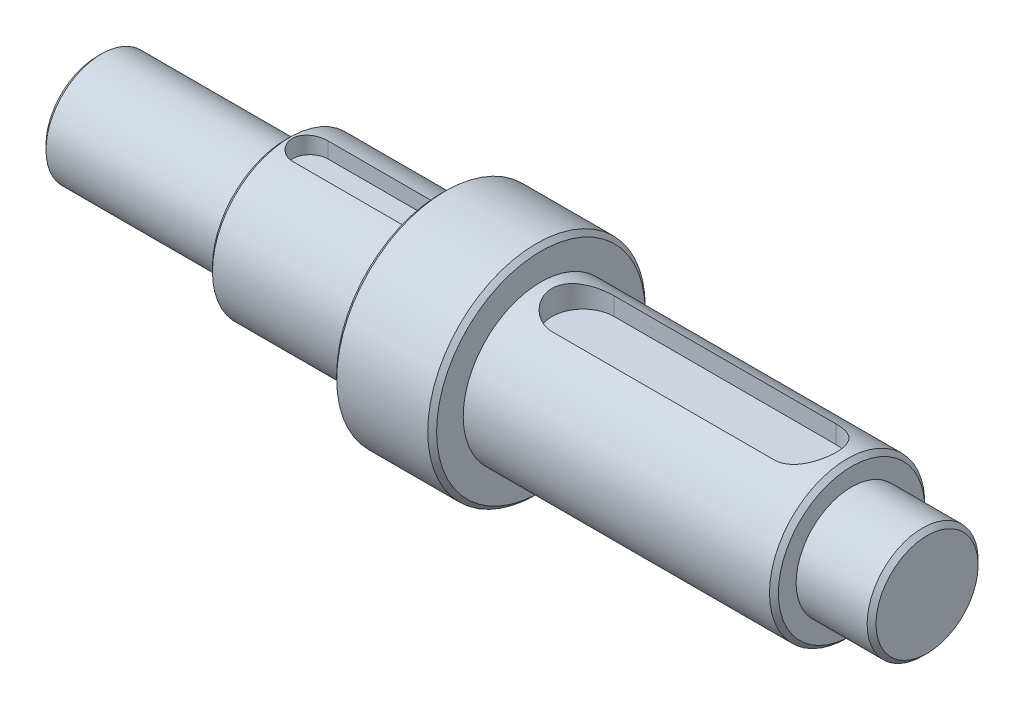
SolidWorks part; units mm, degrees
ref_plane "Front Plane" through (0, 0, 0) normal (0, 0, 1) x (1, 0, 0)
ref_plane "Top Plane" through (0, 0, 0) normal (0, 1, 0) x (1, 0, 0)
ref_plane "Right Plane" through (0, 0, 0) normal (1, 0, 0) x (0, 0, -1)
sketch "Sketch1" plane through (0, 0, 0) normal (0, 0, 1) x (1, 0, 0)
  line L0 (-92.2274, 0) -> (191.9279, 0) construction
  line L1 (-68.9095, 0) -> (-68.9095, 11.5)
  line L2 (-67.9095, 12.5) -> (-26.4095, 12.5)
  line L3 (118.0905, 11.5) -> (118.0905, 0)
  line L4 (-26.4095, 12.5) -> (-26.4095, 16.5)
  line L5 (-25.4095, 17.5) -> (8.5905, 17.5)
  line L6 (8.5905, 17.5) -> (8.5905, 23.5)
  line L7 (9.5905, 24.5) -> (30.0905, 24.5)
  line L8 (31.0905, 23.5) -> (31.0905, 17.5)
  line L9 (31.0905, 17.5) -> (100.0905, 17.5)
  line L10 (101.0905, 16.5) -> (101.0905, 12.5)
  line L11 (101.0905, 12.5) -> (117.0905, 12.5)
  line L12 (-68.9095, 11.5) -> (-67.9095, 12.5)
  line L13 (-26.4095, 16.5) -> (-25.4095, 17.5)
  line L14 (8.5905, 23.5) -> (9.5905, 24.5)
  line L15 (30.0905, 24.5) -> (31.0905, 23.5)
  line L16 (100.0905, 17.5) -> (101.0905, 16.5)
  line L17 (117.0905, 12.5) -> (118.0905, 11.5)
  line L18 (-68.9095, 0) -> (118.0905, 0)
  point P4 (-68.9095, 12.5)
  point P5 (-8.9095, 12.5)
  point P6 (118.0905, 12.5)
  point P8 (61.0905, 12.5)
  point P9 (101.0905, 12.5)
  point P10 (8.5905, 12.5)
  point P11 (31.0905, 12.5)
  point P12 (-26.4095, 12.5)
  point P13 (-51.9095, 12.5)
  point P15 (-26.4095, 17.5)
  point P18 (8.5905, 24.5)
  point P19 (31.0905, 24.5)
  point P21 (101.0905, 17.5)
  dimension "D1" = 30
  dimension "D2" = 12.5
  dimension "D3" = 60
  dimension "D4" = 130
  dimension "D5" = 170
  dimension "D6" = 17.5
  dimension "D7" = 17.5
  dimension "D8" = 17
  dimension "D9" = 17
  dimension "D10" = 5
  dimension "D11" = 7
  dimension "D12" = 5
revolve "Revolve1" add sketch "Sketch1" angle 360 about L0
ref_plane "Plane1" through (0, 17.5, 0) normal (0, 1, 0) x (1, 0, 0)
sketch "Sketch2" plane through (0, 17.5, 0) normal (0, 1, 0) x (1, 0, 0)
  line L3 (-20.9095, 0) -> (4.0905, 0) construction
  line L4 (-20.9095, 4) -> (4.0905, 4)
  line L5 (-20.9095, -4) -> (4.0905, -4)
  arc A0 (-20.9095, 4) -> (-20.9095, -4) centre (-20.9095, 0) ccw
  arc A1 (4.0905, -4) -> (4.0905, 4) centre (4.0905, 0) ccw
  point P8 (-8.4095, 0)
  dimension "D1" = 25
  dimension "D2" = 8
extrude "Cut-Extrude1" cut sketch "Sketch2" against normal blind 4
sketch "Sketch3" plane through (0, 17.5, 0) normal (0, 1, 0) x (1, 0, 0)
  line L3 (40.5905, 0) -> (90.5905, 0) construction
  line L4 (40.5905, 7) -> (90.5905, 7)
  line L5 (40.5905, -7) -> (90.5905, -7)
  arc A0 (40.5905, 7) -> (40.5905, -7) centre (40.5905, 0) ccw
  arc A1 (90.5905, -7) -> (90.5905, 7) centre (90.5905, 0) ccw
  point P8 (65.5905, 0)
  dimension "D1" = 50
  dimension "D2" = 14
extrude "Cut-Extrude2" cut sketch "Sketch3" against normal blind 5.5
